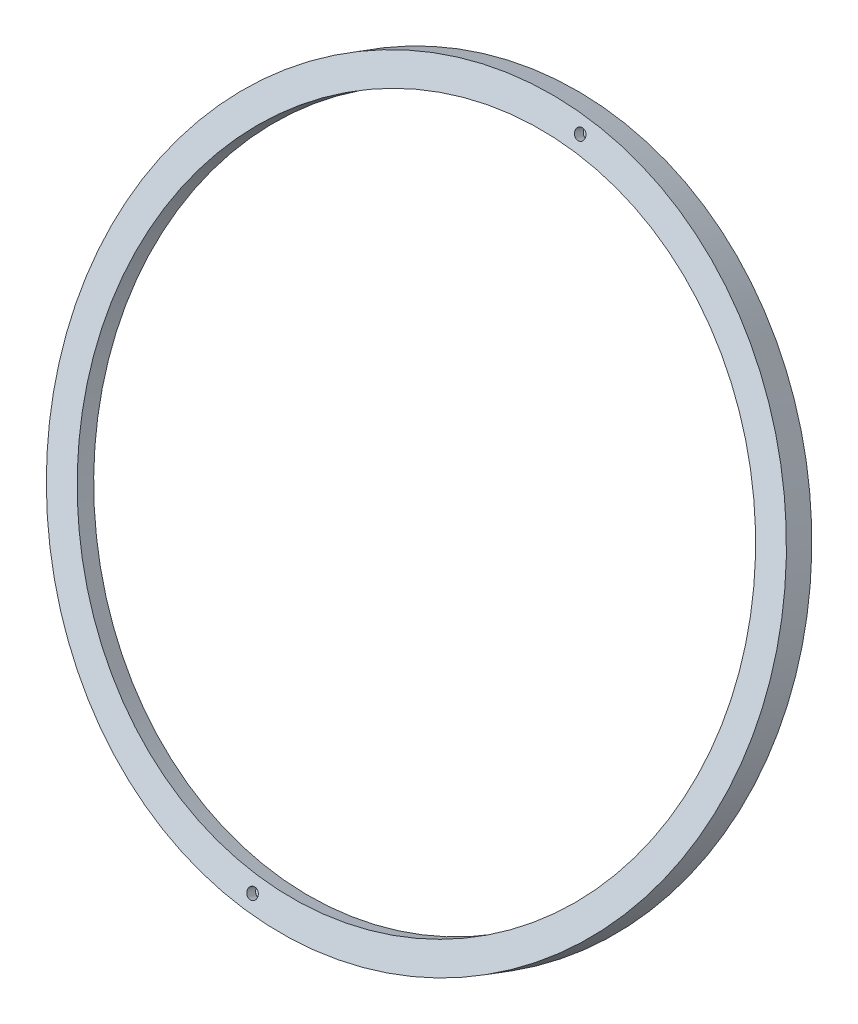
SolidWorks part; units mm, degrees
ref_plane "Plan de face" through (0, 0, 0) normal (0, 0, 1) x (1, 0, 0)
ref_plane "Plan de dessus" through (0, 0, 0) normal (0, 1, 0) x (1, 0, 0)
ref_plane "Plan de droite" through (0, 0, 0) normal (1, 0, 0) x (0, 0, -1)
ref_plane "Plan1" through (0, -1.4222, 0.591) normal (0, 0.9234, -0.3838) x (-1, 0, 0)
sketch "Esquisse1" plane through (0, -1.4222, 0.591) normal (0, 0.9234, -0.3838) x (-1, 0, 0)
  line L0 (-40.3856, 380.5243) -> (7.522, 383.5012)
  line L1 (7.522, 383.5012) -> (7.2553, 387.7929)
  line L2 (7.2553, 387.7929) -> (-40.6523, 384.816)
  line L3 (-40.6523, 384.816) -> (-40.3856, 380.5243)
  line L4 (7.6832, 380.9064) -> (7.094, 390.3877) construction
  dimension "D1" = 96
revolve "Révolution1" add sketch "Esquisse1" angle 360 about L4
hole_wizard "Perçage1" positions "Esquisse3" profile "Esquisse2" legacy
sketch "Esquisse3" plane through (23.9766, 148.0742, 356.3088) normal (0.062, 0.383, 0.9217) x (0.9981, -0.0238, -0.0573)
  point P0 (-25.2645, 44.0632)
  dimension "D1" = 46
sketch "Esquisse2" plane through (-1.2393, 189.365, 340.846) normal (0.6692, 0.6692, -0.3231) x (0.7405, -0.6368, 0.2148)
  line L0 (0, 0) -> (0, 1.5)
  line L1 (0, 1.5) -> (0.75, 1.5)
  line L2 (0.75, 1.5) -> (0.75, 0)
  line L3 (0.75, 0) -> (0, 0)
  line L4 (0, 110) -> (0, -10) construction
  dimension "Diamètre" = 1.5
  dimension "Profondeur" = 1.5
pattern_circular "Répétition circulaire1" count 2 over 360 about axis through (-31.2318, -0.6774, 2.3832) along (0.062, 0.383, 0.9217) of "Perçage1"
hole_wizard "Perçage3" positions "Esquisse7" profile "Esquisse6" legacy
sketch "Esquisse7" plane through (23.7099, 146.4273, 352.3457) normal (-0.062, -0.383, -0.9217) x (-0.9981, 0.0238, 0.0573)
  point P0 (31.2921, -1.5401)
sketch "Esquisse6" plane through (-7.522, 145.7498, 354.7288) normal (0.6692, 0.6692, -0.3231) x (-0.7405, 0.6368, -0.2148)
  line L0 (0, 0) -> (0, 41.4195)
  line L1 (0, 41.4195) -> (44, 41.4195)
  line L2 (44, 41.4195) -> (44, 1.5)
  line L3 (44, 1.5) -> (46, 1.5)
  line L4 (46, 1.5) -> (46, 0)
  line L5 (46, 0) -> (0, 0)
  line L6 (0, -6.13) -> (0, 109.2824) construction
  line L7 (-44, 1.5) -> (-46, 1.5) construction
  line L8 (0, 41.4195) -> (-44, 41.4195) construction
  dimension "Diamètre" = 88
  dimension "Profondeur" = 41.4195
  dimension "Diamètre contre-pointe" = 92
  dimension "Profondeur contre-pointe" = 1.5
